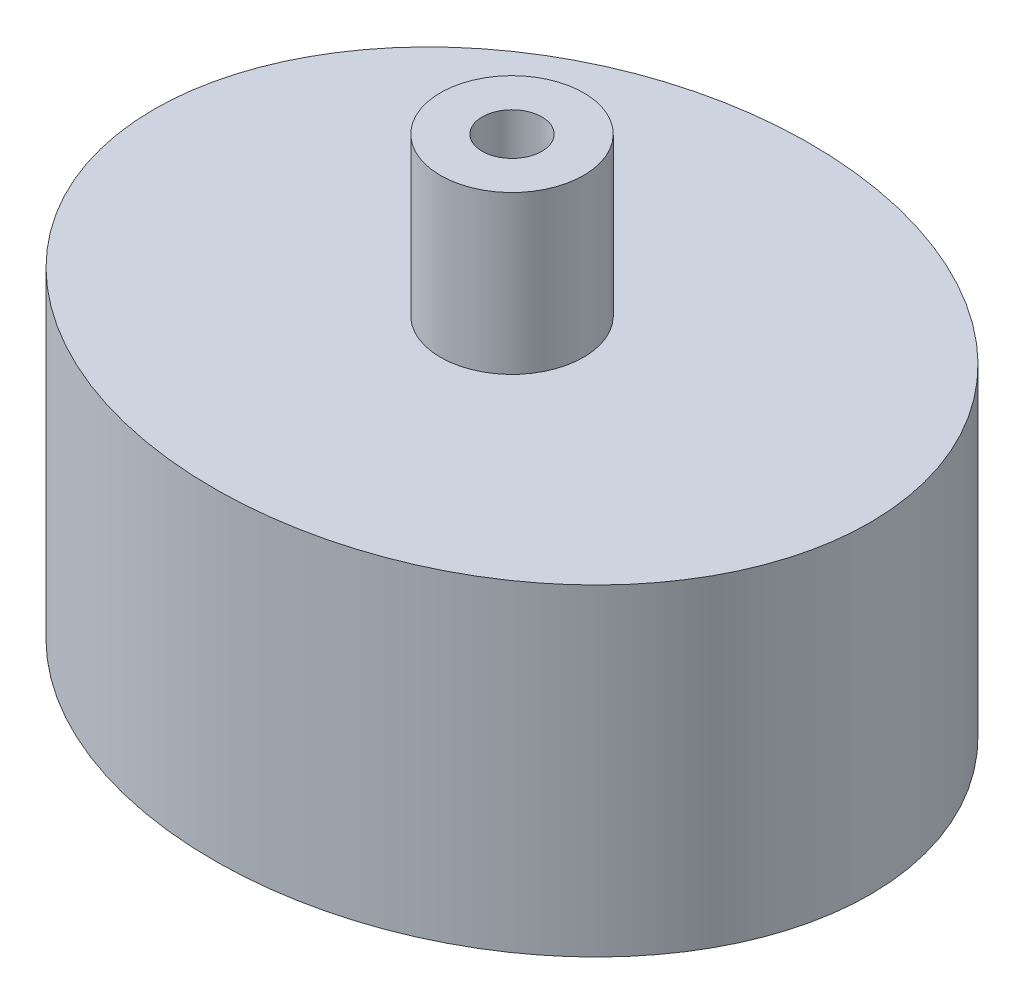
SolidWorks part; units mm, degrees
ref_plane "Front Plane" through (0, 0, 0) normal (0, 0, 1) x (1, 0, 0)
ref_plane "Top Plane" through (0, 0, 0) normal (0, 1, 0) x (1, 0, 0)
ref_plane "Right Plane" through (0, 0, 0) normal (1, 0, 0) x (0, 0, -1)
sketch "Sketch1" plane through (0, 0, 0) normal (0, 1, 0) x (1, 0, 0)
  circle A0 centre (0, 0) radius 25.4
  dimension "D1" = 50.8
extrude "Boss-Extrude1" add sketch "Sketch1" along normal blind 5.842
sketch "Sketch2" plane through (0, 5.842, 0) normal (0, 1, 0) x (1, 0, 0)
  ellipse E0 centre (0, 0) end of major axis (-76.2, 0) minor radius 63.5
  dimension "D1" = 127
  dimension "D2" = 152.4
extrude "Boss-Extrude2" add sketch "Sketch2" along normal blind 68.58
sketch "Sketch3" plane through (0, 74.422, 0) normal (0, 1, 0) x (1, 0, 0)
  circle A0 centre (0, 0) radius 15.24
  dimension "D1" = 30.48
extrude "Boss-Extrude3" add sketch "Sketch3" along normal blind 33.528
sketch "Sketch4" plane through (0, 0, 0) normal (0, 1, 0) x (1, 0, 0)
  circle A0 centre (0, 0) radius 6.35
  dimension "D1" = 12.7
extrude "Cut-Extrude2" cut sketch "Sketch4" against normal through all and the other way through all
